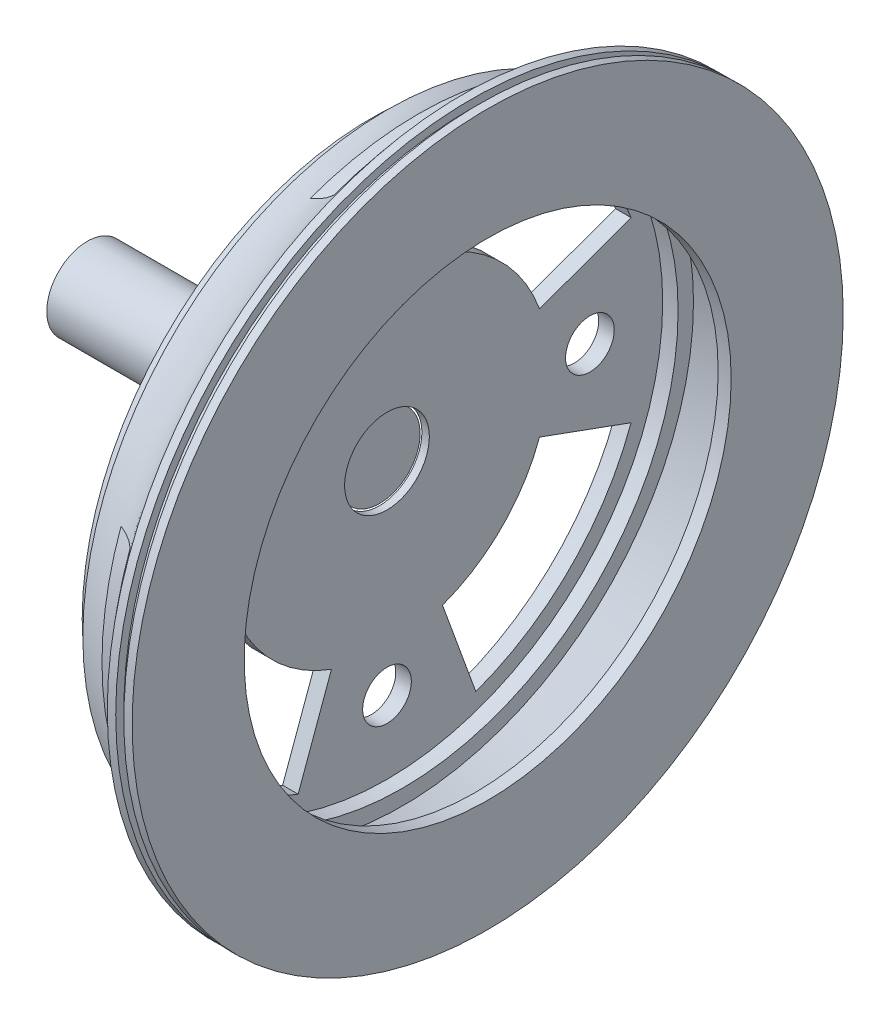
SolidWorks part; units mm, degrees
ref_plane "Front Plane" through (0, 0, 0) normal (0, 0, 1) x (1, 0, 0)
ref_plane "Top Plane" through (0, 0, 0) normal (0, 1, 0) x (1, 0, 0)
ref_plane "Right Plane" through (0, 0, 0) normal (1, 0, 0) x (0, 0, -1)
sketch "Sketch1" plane through (0, 0, 0) normal (0, 1, 0) x (1, 0, 0)
  line L0 (0, 0) -> (0, 21.9026)
  line L1 (0, 21.9026) -> (-0.5117, 21.9026)
  line L2 (-0.5117, 21.9026) -> (-0.5117, 21.3909)
  line L3 (-0.5117, 21.3909) -> (-1.0235, 21.3909)
  line L4 (-1.0235, 21.3909) -> (-1.0235, 21.8905)
  line L5 (-1.0235, 21.8905) -> (-1.5444, 21.8905)
  line L6 (0, 0) -> (-20.7379, 0)
  line L7 (0, 0) -> (-6.1381, 0)
  line L10 (-6.2029, 18.7375) -> (-6.2029, 17.8181)
  line L11 (-6.2029, 17.8181) -> (-7.1616, 17.8181)
  line L12 (-7.1616, 2.6089) -> (-7.1616, 17.8181)
  line L13 (-7.1616, 2.6089) -> (-6.2029, 2.6089)
  line L14 (-6.2029, 2.6089) -> (-6.2029, 16.9849)
  line L15 (-6.2029, 16.9849) -> (-5.2548, 16.9849)
  line L16 (-5.2548, 16.9849) -> (-5.2548, 17.9331)
  line L17 (-5.2548, 17.9331) -> (-0.8014, 20.7487)
  line L19 (-0.8014, 20.7487) -> (-0.8014, 0)
  spline S0 degree 2 poles (-6.2029, 18.7375) (-3.3058, 19.5005) (-1.5444, 21.8905) knots 0 0 0 1 1 1
revolve "Revolve5" add sketch "Sketch1" angle 360 about L6
sketch "Sketch6" plane through (-7.1616, 0, 0) normal (-1, 0, 0) x (0, 0, 1)
  circle A0 centre (0, 0) radius 12.5
  circle A1 centre (0, 12.5) radius 1.5
extrude "Cut-Extrude2" cut sketch "Sketch6" against normal blind 10 contours A0 A1 | A0 A1
sketch "Sketch7" plane through (-7.1616, 0, 0) normal (-1, 0, 0) x (0, 0, 1)
  circle A0 centre (0, 0) radius 12.5
  circle A1 centre (12.5, 0) radius 1.5
  circle A2 centre (0, -12.5) radius 1.5
  circle A3 centre (-12.5, 0) radius 1.5
extrude "Cut-Extrude3" cut sketch "Sketch7" against normal blind 10 contours A0 A3 | A0 A3 | A0 A2 | A0 A2 | A0 A1 | A0 A1
sketch "Sketch9" plane through (0, 0, 0) normal (1, 0, 0) x (0, 0, -1)
  circle A0 centre (0, 0) radius 15
extrude "Cut-Extrude6" cut sketch "Sketch9" against normal blind 2
sketch "Sketch10" plane through (-7.1616, 0, 0) normal (-1, 0, 0) x (0, 0, 1)
  circle A1 centre (0, 0) radius 8
  circle A2 centre (0, 0) radius 7
extrude "Cut-Extrude10" cut sketch "Sketch10" against normal blind 0.5 contours A2
sketch "Sketch11" plane through (-7.1616, 0, 0) normal (-1, 0, 0) x (0, 0, 1)
  circle A0 centre (0, 0) radius 8
extrude "Cut-Extrude11" cut sketch "Sketch11" against normal blind 0.3
sketch "Sketch12" plane through (-7.1616, 0, 0) normal (-1, 0, 0) x (0, 0, 1)
  line L0 (6.6694, 18.324) -> (7.1824, 19.7335)
  line L5 (-6.6694, 18.324) -> (-7.2151, 19.8234)
  arc A2 (-7.1824, 19.7335) -> (7.1824, 19.7335) centre (0, 0) cw
  arc A3 (-6.6694, 18.324) -> (6.6694, 18.324) centre (0, 0) cw
extrude "Cut-Extrude12" cut sketch "Sketch12" against normal blind 5.5 contours L5 A3 L0 A2
pattern_circular "CirPattern1" count 4 every 90 about axis through (-6.6616, 0, 0) along (-1, 0, 0) of "Cut-Extrude12"
sketch "Sketch13" plane through (-7.1616, 0, 0) normal (-1, 0, 0) x (0, 0, 1)
  line L2 (3.4202, 9.3969) -> (5.4723, 15.0351)
  line L3 (9.3969, 3.4202) -> (15.0351, 5.4723)
  arc A0 (5.4723, 15.0351) -> (15.0351, 5.4723) centre (0, 0) cw
  arc A1 (3.4202, 9.3969) -> (9.3969, 3.4202) centre (0, 0) cw
extrude "Cut-Extrude13" cut sketch "Sketch13" against normal blind 5.5 contours L3 A0 L2 A1
pattern_circular "CirPattern2" count 4 every 90 about axis through (-6.6616, 0, 0) along (-1, 0, 0) of "Cut-Extrude13"
sketch "Sketch14" plane through (-6.6616, 0, 0) normal (-1, 0, 0) x (0, 0, 1)
  circle A0 centre (0, 0) radius 2.5
extrude "Boss-Extrude1" add sketch "Sketch14" along normal blind 18 separate body
